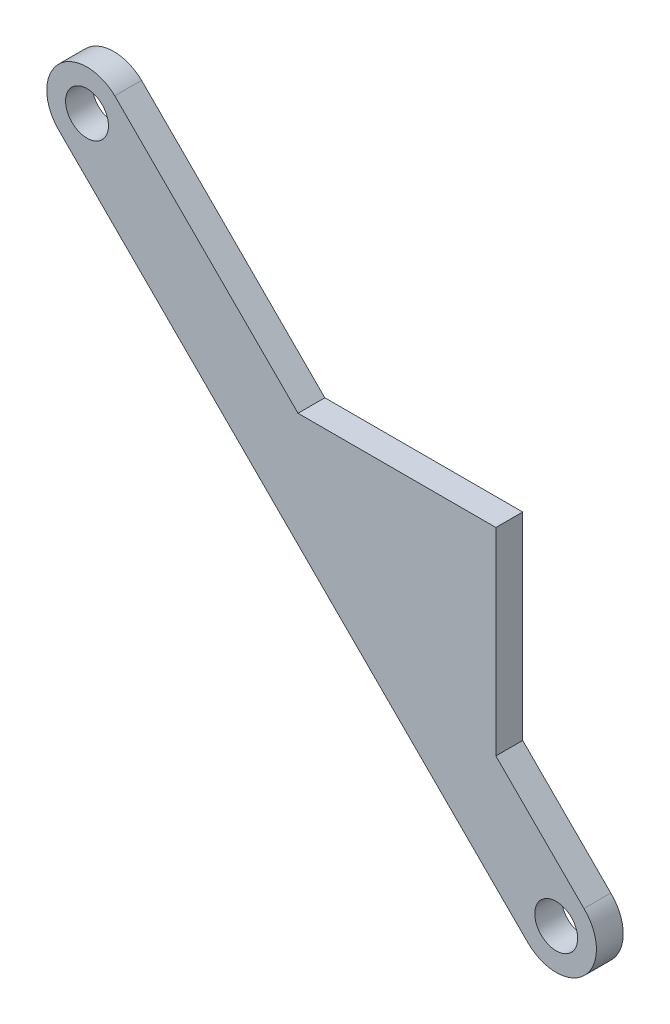
SolidWorks part; units mm, degrees
ref_plane "Front" through (0, 0, 0) normal (0, 0, 1) x (1, 0, 0)
ref_plane "Top" through (0, 0, 0) normal (0, 1, 0) x (1, 0, 0)
ref_plane "Right" through (0, 0, 0) normal (1, 0, 0) x (0, 0, -1)
sketch "Эскиз1" plane through (0, 0, 0) normal (0, 0, 1) x (1, 0, 0)
  line L0 (-17.5, 17.5) -> (-15.4291, 19.6706) construction
  line L1 (-17.5, -17.5) -> (17.5, -17.5) construction
  line L2 (-17.5, -17.5) -> (-17.5, 17.5) construction
  line L3 (-17.5, 17.5) -> (17.5, 17.5) construction
  line L4 (17.5, -17.5) -> (17.5, 17.5) construction
  line L5 (2.7585, -7) -> (0, -4.2415)
  line L6 (-17.5, 17.5) -> (-16.3686, 16.3686) construction
  line L7 (-17.5, 17.5) -> (-19.5709, 15.3294) construction
  line L8 (17.5, -17.5) -> (15.4291, -19.6706) construction
  line L9 (17.5, -17.5) -> (19.5709, -15.3294) construction
  line L10 (19.5709, -15.3294) -> (13, -8.7585)
  line L11 (-19.5709, 15.3294) -> (0, -4.2415)
  line L12 (16.3686, -16.3686) -> (17.5, -17.5) construction
  line L15 (-1.7585, 6) -> (13, 6)
  line L16 (13, -8.7585) -> (13, 6)
  line L18 (-1.7585, 6) -> (-15.4291, 19.6706)
  line L19 (2.7585, -7) -> (15.4291, -19.6706)
  circle A0 centre (-17.5, 17.5) radius 1.6
  circle A1 centre (17.5, -17.5) radius 1.6
  arc A2 (15.3294, -19.5709) -> (19.5709, -15.3294) centre (17.5, -17.5) ccw
  arc A3 (-15.3294, 19.5709) -> (-19.5709, 15.3294) centre (-17.5, 17.5) ccw
  point P0 (0, 0)
  point P8 (0, 0)
  dimension "D1" = 35
  dimension "D2" = 35
  dimension "D4" = 13
  dimension "D6" = 6
extrude "Бобышка-Вытянуть1" add sketch "Эскиз1" along normal blind 2
